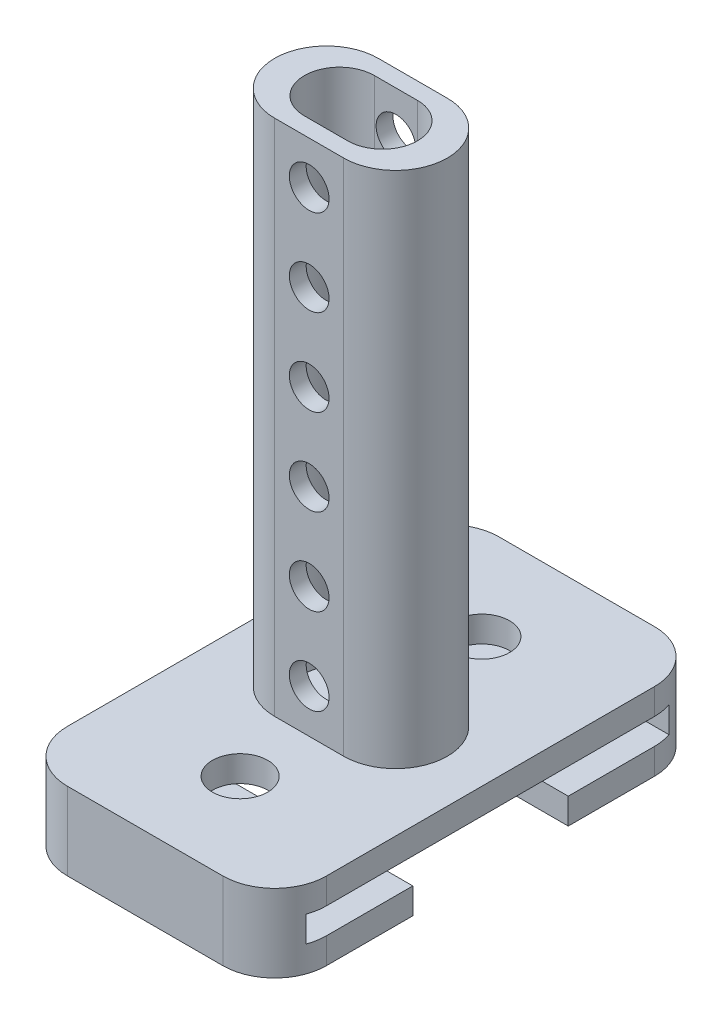
SolidWorks part; units mm, degrees
ref_plane "前视基准面" through (0, 0, 0) normal (0, 0, 1) x (1, 0, 0)
ref_plane "上视基准面" through (0, 0, 0) normal (0, 1, 0) x (1, 0, 0)
ref_plane "右视基准面" through (0, 0, 0) normal (1, 0, 0) x (0, 0, -1)
other "Configuration Table"
sketch "草图2" plane through (0, 0, 0) normal (0, 1, 0) x (1, 0, 0)
  line L0 (-2.5, 0) -> (2.5, 0) construction
  line L1 (-2.5, 4.05) -> (2.5, 4.05)
  line L2 (-2.5, -4.05) -> (2.5, -4.05)
  line L3 (-4, 0) -> (4, 0) construction
  line L4 (-4, 6) -> (4, 6)
  line L5 (-4, -6) -> (4, -6)
  arc A0 (-2.5, 4.05) -> (-2.5, -4.05) centre (-2.5, 0) ccw
  arc A1 (2.5, -4.05) -> (2.5, 4.05) centre (2.5, 0) ccw
  arc A2 (-4, 6) -> (-4, -6) centre (-4, 0) ccw
  arc A3 (4, -6) -> (4, 6) centre (4, 0) ccw
  point P2 (0, 0)
  point P10 (0, 0)
  dimension "D1" = 8.1
  dimension "D2" = 5
  dimension "D3" = 8
  dimension "D4" = 12
extrude "凸台-拉伸1" add sketch "草图2" along normal blind 60
sketch "草图3" plane through (0, 0, 6) normal (0, 0, 1) x (1, 0, 0)
  circle A0 centre (0, 55.0492) radius 2.3
  circle A1 centre (0, 45.0492) radius 2.3
  circle A2 centre (0, 35.0492) radius 2.3
  circle A3 centre (0, 25.0492) radius 2.3
  circle A4 centre (0, 15.0492) radius 2.3
  circle A5 centre (0, 5.0492) radius 2.3
  dimension "D1" = 6
extrude "切除-拉伸1" cut sketch "草图3" against normal blind 30
sketch "草图4" plane through (0, 0, 0) normal (0, -1, 0) x (1, 0, 0)
  line L1 (-15, 25) -> (15, 25)
  line L2 (-15, 25) -> (-15, -25)
  line L3 (-15, -25) -> (15, -25)
  line L4 (15, 25) -> (15, -25)
  line L5 (-15, 25) -> (15, -25) construction
  line L6 (-15, -25) -> (15, 25) construction
  point P0 (0, 0)
  dimension "D1" = 50
  dimension "D2" = 30
extrude "凸台-拉伸2" add sketch "草图4" along normal blind 3
sketch "草图5" plane through (0, 0, 0) normal (1, 0, 0) x (0, 0, -1)
  line L0 (0, 0) -> (0, -16.9752) construction
  line L1 (-25, -3) -> (-21, -3)
  line L2 (-25, -3) -> (-25, -6)
  line L4 (-21, -3) -> (-21, -6)
  line L5 (-21, -6) -> (-9, -6)
  line L6 (-25, -6) -> (-25, -9)
  line L7 (-25, -9) -> (-9, -9)
  line L8 (-9, -6) -> (-9, -9)
  line L9 (25, -3) -> (21, -3)
  line L10 (21, -3) -> (21, -6)
  line L11 (21, -6) -> (9, -6)
  line L12 (9, -6) -> (9, -9)
  line L13 (25, -9) -> (9, -9)
  line L14 (25, -6) -> (25, -9)
  line L15 (25, -3) -> (25, -6)
  dimension "D2" = 4
  dimension "D3" = 3
  dimension "D4" = 16
extrude "凸台-拉伸3" add sketch "草图5" along normal mid plane 30
sketch "草图6" plane through (0, 0, 0) normal (0, 1, 0) x (1, 0, 0)
  line L5 (-22.2361, 30.8978) -> (25.4214, 30.8978)
  line L6 (-22.2361, 30.8978) -> (-22.2361, -30.6954)
  line L7 (-22.2361, -30.6954) -> (25.4214, -30.6954)
  line L8 (15, -25) -> (15, 25)
  line L9 (15, 25) -> (-15, 25)
  line L10 (-15, 25) -> (-15, -25)
  line L11 (-15, -25) -> (15, -25)
  line L12 (15, -19) -> (15, 19)
  line L13 (9, 25) -> (-9, 25)
  line L14 (-15, 19) -> (-15, -19)
  line L15 (-9, -25) -> (9, -25)
  line L16 (25.4214, 30.8978) -> (25.4214, -30.6954)
  arc A0 (-15, -19) -> (-9, -25) centre (-9, -19) ccw
  arc A1 (15, -19) -> (9, -25) centre (9, -19) cw
  arc A2 (15, 19) -> (9, 25) centre (9, 19) ccw
  arc A3 (-9, 25) -> (-15, 19) centre (-9, 19) ccw
  dimension "D2" = 6
  dimension "D1" = 0
extrude "切除-拉伸2" cut sketch "草图6" against normal blind 30
sketch "草图7" plane through (0, 0, 0) normal (0, 1, 0) x (1, 0, 0)
  line L0 (0, 0) -> (23.4863, 0) construction
  line L1 (0, 0) -> (0, 18.1987) construction
  circle A0 centre (0, 14) radius 3.2
  circle A1 centre (0, -14) radius 3.2
  dimension "D1" = 14
  dimension "D2" = 6.4
extrude "切除-拉伸3" cut sketch "草图7" against normal blind 3
